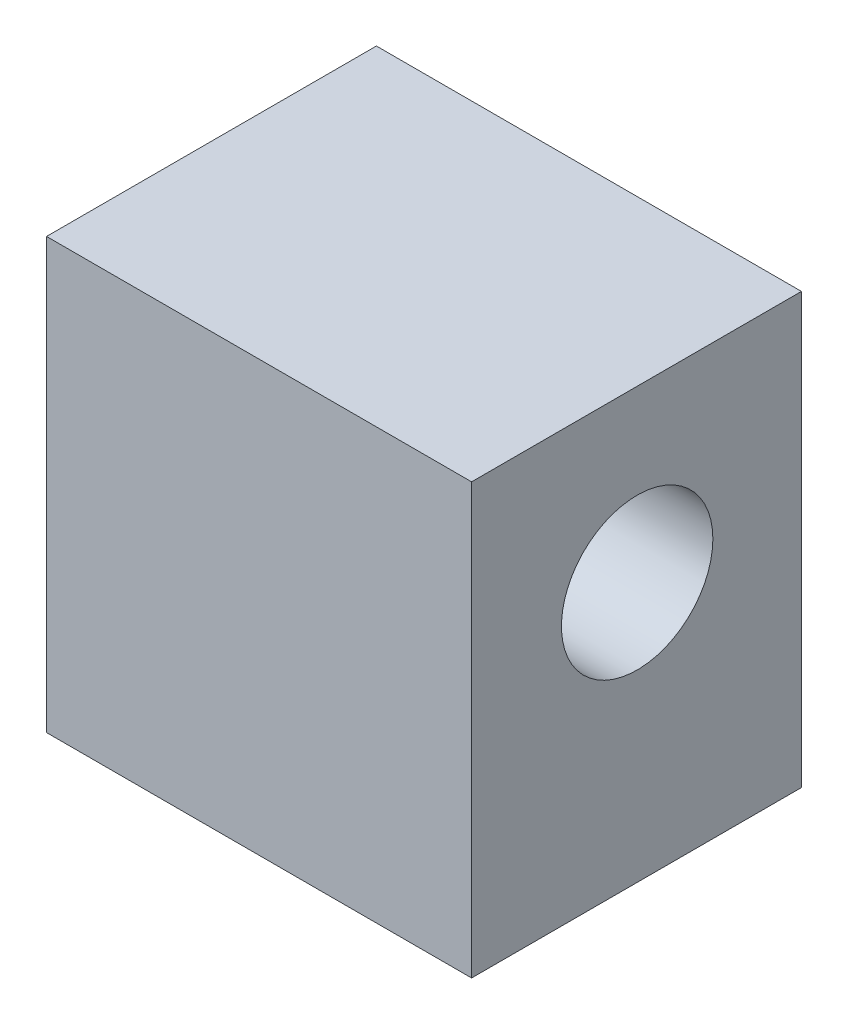
SolidWorks part; units mm, degrees
ref_plane "Front Plane" through (0, 0, 0) normal (0, 0, 1) x (1, 0, 0)
ref_plane "Top Plane" through (0, 0, 0) normal (0, 1, 0) x (1, 0, 0)
ref_plane "Right Plane" through (0, 0, 0) normal (1, 0, 0) x (0, 0, -1)
sketch "Sketch1" plane through (0, 0, 0) normal (0, 0, 1) x (1, 0, 0)
  line L1 (-168.4456, 172.5889) -> (24.8521, 172.5889)
  line L2 (-168.4456, 172.5889) -> (-168.4456, -22.8271)
  line L3 (-168.4456, -22.8271) -> (24.8521, -22.8271)
  line L4 (24.8521, 172.5889) -> (24.8521, -22.8271)
  point P4 (-168.4456, 172.5889)
extrude "Boss-Extrude1" add sketch "Sketch1" along normal blind 150
sketch "Sketch2" plane through (24.8521, 0, 0) normal (1, 0, 0) x (0, 0, -1)
  circle A0 centre (-74.7082, 95.2595) radius 34.4331
  point P2 (-74.7082, 95.2595)
extrude "Cut-Extrude1" cut sketch "Sketch2" against normal through all
